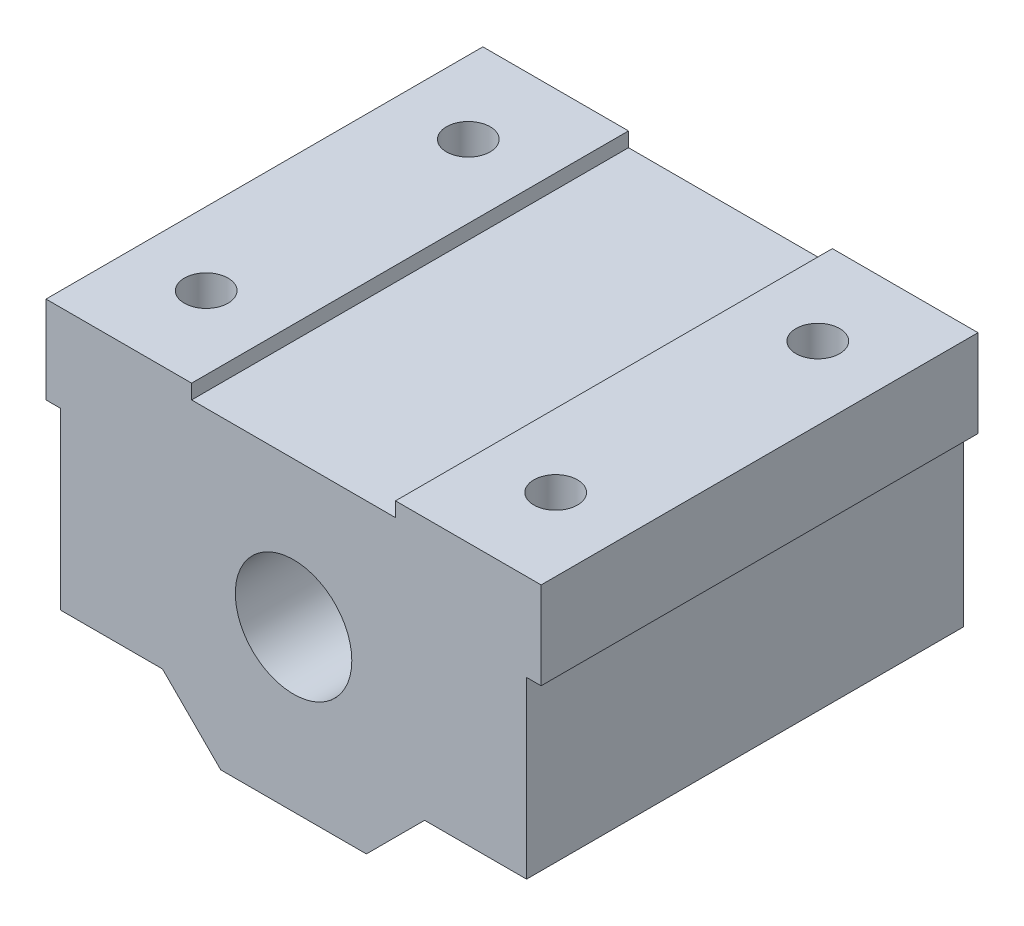
SolidWorks part; units mm, degrees
ref_plane "Front Plane" through (0, 0, 0) normal (0, 0, 1) x (1, 0, 0)
ref_plane "Top Plane" through (0, 0, 0) normal (0, 1, 0) x (1, 0, 0)
ref_plane "Right Plane" through (0, 0, 0) normal (1, 0, 0) x (0, 0, -1)
sketch "Sketch1" plane through (0, 0, 0) normal (0, 0, 1) x (1, 0, 0)
  line L0 (-16, -7) -> (-9, -7)
  line L1 (-5, -11) -> (5, -11)
  line L2 (-17, 5) -> (-17, 11)
  line L3 (-17, 11) -> (-7, 11)
  line L4 (17, 5) -> (17, 11)
  line L5 (-17, -11) -> (17, 11) construction
  line L6 (-17, 11) -> (17, -11) construction
  line L7 (-9, -7) -> (-5, -11)
  line L8 (9, -7) -> (5, -11)
  line L9 (-7, 10) -> (7, 10)
  line L10 (-16, 5) -> (-16, -7)
  line L11 (16, 5) -> (16, -7)
  line L12 (-16, 5) -> (-17, 5)
  line L13 (16, 5) -> (17, 5)
  line L14 (-7, 10) -> (-7, 11)
  line L15 (7, 10) -> (7, 11)
  line L16 (7, 11) -> (17, 11)
  line L17 (9, -7) -> (16, -7)
  circle A0 centre (0, 0) radius 4
  point P0 (0, 0)
  dimension "D1" = 18
  dimension "D2" = 1
  dimension "D3" = 10
  dimension "D4" = 12
  dimension "D5" = 12
  dimension "D6" = 10
  dimension "D7" = 1
  dimension "D8" = 1
extrude "Boss-Extrude1" add sketch "Sketch1" along normal blind 30 contours L16 L15 L9 L14 L3 L2 L12 L10 L0 L11 L13 L4 A0
sketch "Sketch2" plane through (0, 11, 0) normal (0, 1, 0) x (-1, 0, 0)
  circle A0 centre (12, 24) radius 1.5
  circle A1 centre (12, 6) radius 1.5
  circle A2 centre (-12, 24) radius 1.5
  circle A3 centre (-12, 6) radius 1.5
  point P0 (0, 15)
extrude "Cut-Extrude1" cut sketch "Sketch2" against normal blind 30
